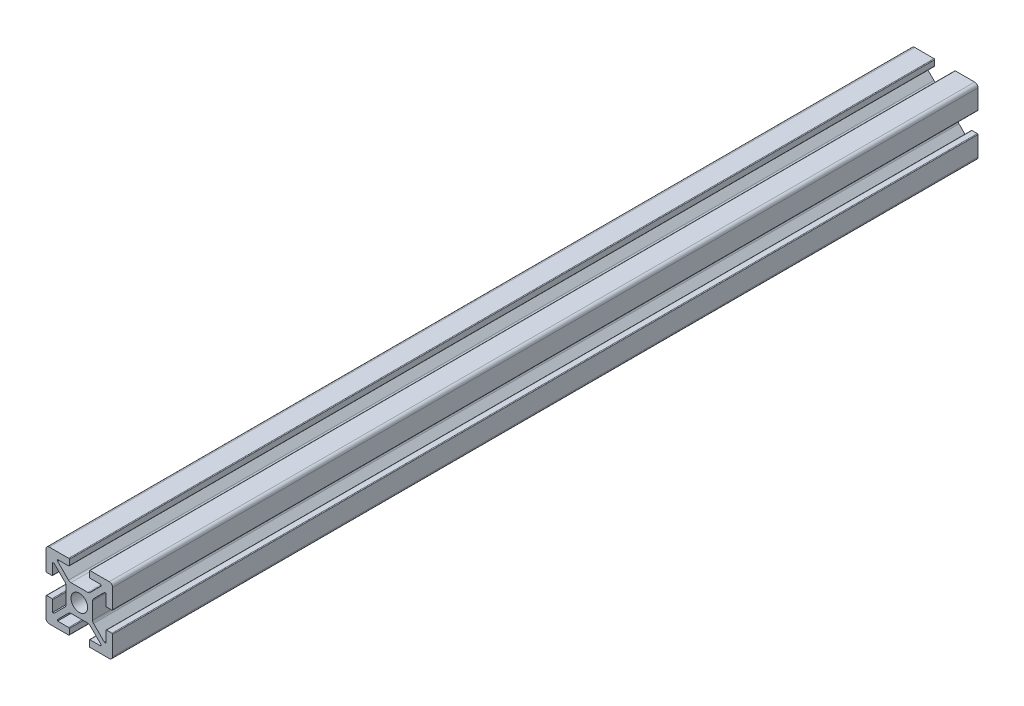
SolidWorks part; units mm, degrees
ref_plane "Front Plane" through (0, 0, 0) normal (0, 0, 1) x (1, 0, 0)
ref_plane "Top Plane" through (0, 0, 0) normal (0, 1, 0) x (1, 0, 0)
ref_plane "Right Plane" through (0, 0, 0) normal (1, 0, 0) x (0, 0, -1)
sketch "Sketch1" plane through (0, 0, 0) normal (0, 0, 1) x (1, 0, 0)
  line L0 (0.2, 13) -> (1.8, 13)
  line L1 (13.2, 0) -> (19, 0)
  line L2 (0, 13.2) -> (0, 19)
  line L3 (1, 20) -> (6.8, 20)
  line L4 (20, 1) -> (20, 6.8)
  line L5 (2, 13.2) -> (2, 16.5)
  line L6 (2, 16.5) -> (2.4393, 16.5)
  line L7 (2.4393, 16.5) -> (5.7071, 13.2322)
  line L8 (6, 12.5251) -> (6, 7.4749)
  line L11 (7.4749, 14) -> (10, 14)
  line L12 (3.5, 17.5607) -> (6.7678, 14.2929)
  line L13 (3.5, 18) -> (3.5, 17.5607)
  line L14 (6.8, 18) -> (3.5, 18)
  line L15 (6.8, 20) -> (1, 20)
  line L16 (7, 19.8) -> (7, 18.2)
  line L17 (19.8, 7) -> (18.2, 7)
  line L18 (20, 6.8) -> (20, 1)
  line L19 (18, 6.8) -> (18, 3.5)
  line L20 (18, 3.5) -> (17.5607, 3.5)
  line L21 (17.5607, 3.5) -> (14.2929, 6.7678)
  line L22 (14, 7.4749) -> (14, 12.5251)
  line L23 (12.5251, 6) -> (10, 6)
  line L24 (16.5, 2.4393) -> (13.2322, 5.7071)
  line L25 (16.5, 2) -> (16.5, 2.4393)
  line L26 (13.2, 2) -> (16.5, 2)
  line L27 (13.2, 0) -> (19, 0)
  line L28 (13, 0.2) -> (13, 1.8)
  line L30 (13, 19.8) -> (13, 18.2)
  line L31 (13.2, 20) -> (19, 20)
  line L32 (13.2, 18) -> (16.5, 18)
  line L33 (16.5, 18) -> (16.5, 17.5607)
  line L34 (16.5, 17.5607) -> (13.2322, 14.2929)
  line L35 (12.5251, 14) -> (10, 14)
  line L36 (17.5607, 16.5) -> (14.2929, 13.2322)
  line L37 (18, 16.5) -> (17.5607, 16.5)
  line L38 (18, 13.2) -> (18, 16.5)
  line L39 (20, 13.2) -> (20, 19)
  line L40 (19.8, 13) -> (18.2, 13)
  line L41 (7, 0.2) -> (7, 1.8)
  line L42 (6.8, 0) -> (1, 0)
  line L43 (6.8, 2) -> (3.5, 2)
  line L44 (3.5, 2) -> (3.5, 2.4393)
  line L45 (3.5, 2.4393) -> (6.7678, 5.7071)
  line L46 (7.4749, 6) -> (10, 6)
  line L47 (2.4393, 3.5) -> (5.7071, 6.7678)
  line L48 (2, 3.5) -> (2.4393, 3.5)
  line L49 (2, 6.8) -> (2, 3.5)
  line L50 (20, 19) -> (20, 13.2)
  line L51 (1, 0) -> (6.8, 0)
  line L52 (0, 6.8) -> (0, 1)
  line L53 (13.2, 20) -> (19, 20)
  line L54 (0.2, 7) -> (1.8, 7)
  arc A0 (20, 1) -> (19, 0) centre (19, 1) cw
  arc A1 (1, 0) -> (0, 1) centre (1, 1) cw
  arc A2 (0, 19) -> (1, 20) centre (1, 19) cw
  arc A3 (20, 19) -> (19, 20) centre (19, 19) ccw
  arc A4 (14.2929, 6.7678) -> (14, 7.4749) centre (15, 7.4749) cw
  arc A5 (12.5251, 6) -> (13.2322, 5.7071) centre (12.5251, 5) cw
  arc A6 (6.7678, 5.7071) -> (7.4749, 6) centre (7.4749, 5) cw
  arc A7 (5.7071, 6.7678) -> (6, 7.4749) centre (5, 7.4749) ccw
  arc A8 (14.2929, 13.2322) -> (14, 12.5251) centre (15, 12.5251) ccw
  arc A9 (13.2322, 14.2929) -> (12.5251, 14) centre (12.5251, 15) cw
  arc A10 (6, 12.5251) -> (5.7071, 13.2322) centre (5, 12.5251) ccw
  arc A11 (7.4749, 14) -> (6.7678, 14.2929) centre (7.4749, 15) cw
  arc A12 (0, 6.8) -> (0.2, 7) centre (0.2, 6.8) cw
  arc A13 (2, 6.8) -> (1.8, 7) centre (1.8, 6.8) ccw
  arc A14 (7, 1.8) -> (6.8, 2) centre (6.8, 1.8) ccw
  arc A15 (7, 0.2) -> (6.8, 0) centre (6.8, 0.2) cw
  arc A16 (13.2, 0) -> (13, 0.2) centre (13.2, 0.2) cw
  arc A17 (13.2, 2) -> (13, 1.8) centre (13.2, 1.8) ccw
  arc A18 (18.2, 7) -> (18, 6.8) centre (18.2, 6.8) ccw
  arc A19 (19.8, 7) -> (20, 6.8) centre (19.8, 6.8) cw
  arc A20 (20, 13.2) -> (19.8, 13) centre (19.8, 13.2) cw
  arc A21 (18, 13.2) -> (18.2, 13) centre (18.2, 13.2) ccw
  arc A22 (13, 19.8) -> (13.2, 20) centre (13.2, 19.8) cw
  arc A23 (13, 18.2) -> (13.2, 18) centre (13.2, 18.2) ccw
  arc A24 (6.8, 18) -> (7, 18.2) centre (6.8, 18.2) ccw
  arc A25 (7, 19.8) -> (6.8, 20) centre (6.8, 19.8) ccw
  arc A26 (1.8, 13) -> (2, 13.2) centre (1.8, 13.2) ccw
  arc A27 (0.2, 13) -> (0, 13.2) centre (0.2, 13.2) cw
  circle A28 centre (10, 10) radius 2.5
  point P19 (2, 13)
  dimension "D1" = 1
  dimension "D4" = 1
  dimension "D5" = 0.2
  dimension "D6" = 0.2
  dimension "D7" = 5
  dimension "D2" = 7
  dimension "D3" = 2
  dimension "D9" = 3.5
extrude "Boss-Extrude1" add sketch "Sketch1" along normal blind 260 contours A27 L0 A26 L5 L6 L7 A10 L8 A7 L47 L48 L49 A13 L54 A12 L52 A1 L42 A15 L41 A14 L43 L44 L45 A6 L46 L23 A5 L24 L25 L26 A17 L28 A16 L1 A0 L4 A19 L17 A18 L19 L20 L21 A4 L22 A8 L36 L37 L38 A21 L40
